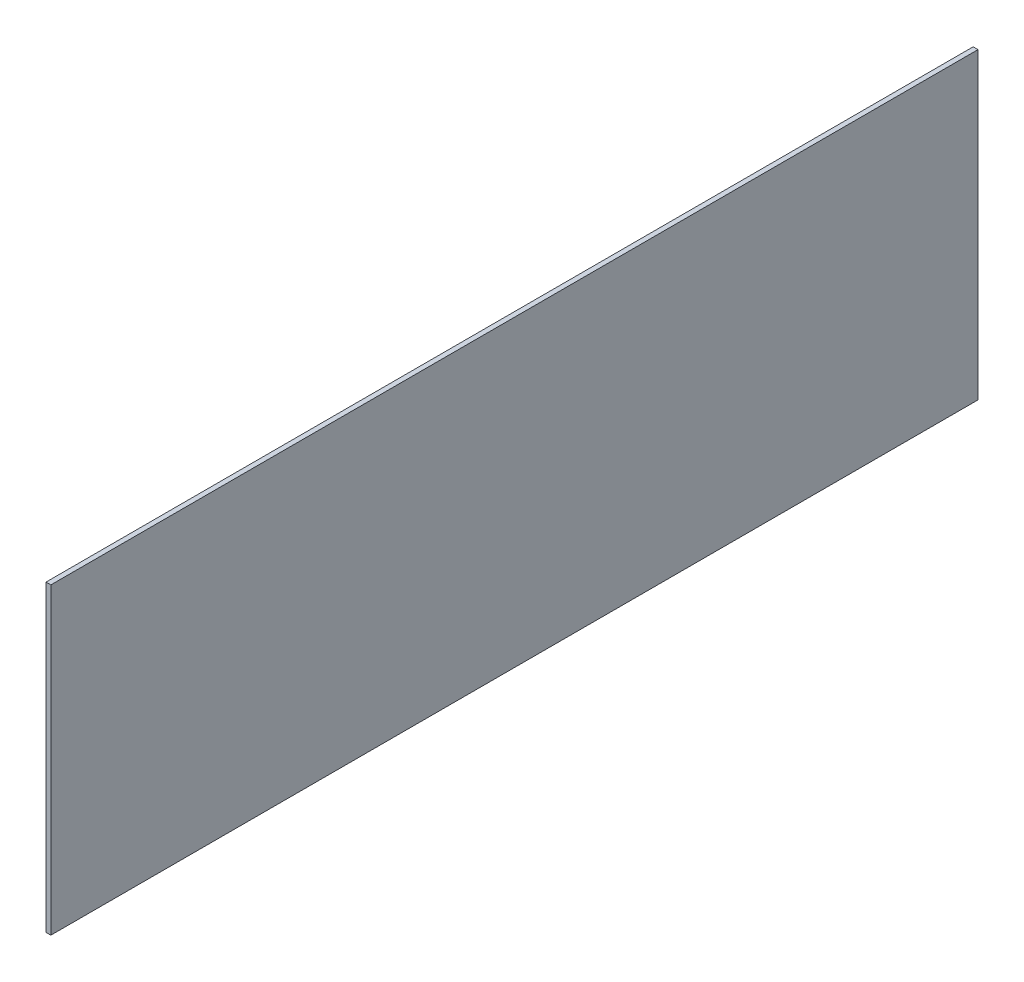
SolidWorks part; units mm, degrees
ref_plane "Front Plane" through (0, 0, 0) normal (0, 0, 1) x (1, 0, 0)
ref_plane "Top Plane" through (0, 0, 0) normal (0, 1, 0) x (1, 0, 0)
ref_plane "Right Plane" through (0, 0, 0) normal (1, 0, 0) x (0, 0, -1)
ref_plane "Plane1" through (532, 0, 0) normal (-1, 0, 0) x (0, -1, 0)
sketch "Sketch1" plane through (532, 0, 0) normal (-1, 0, 0) x (0, -1, 0)
  line L0 (75, 0) -> (-50, 0)
  line L1 (-50, 0) -> (-50, -382)
  line L2 (-50, -382) -> (75, -382)
  line L3 (75, -382) -> (75, 0)
  dimension "D1" = 382
  dimension "D2" = 125
extrude "Boss-Extrude1" add sketch "Sketch1" against normal blind 2
